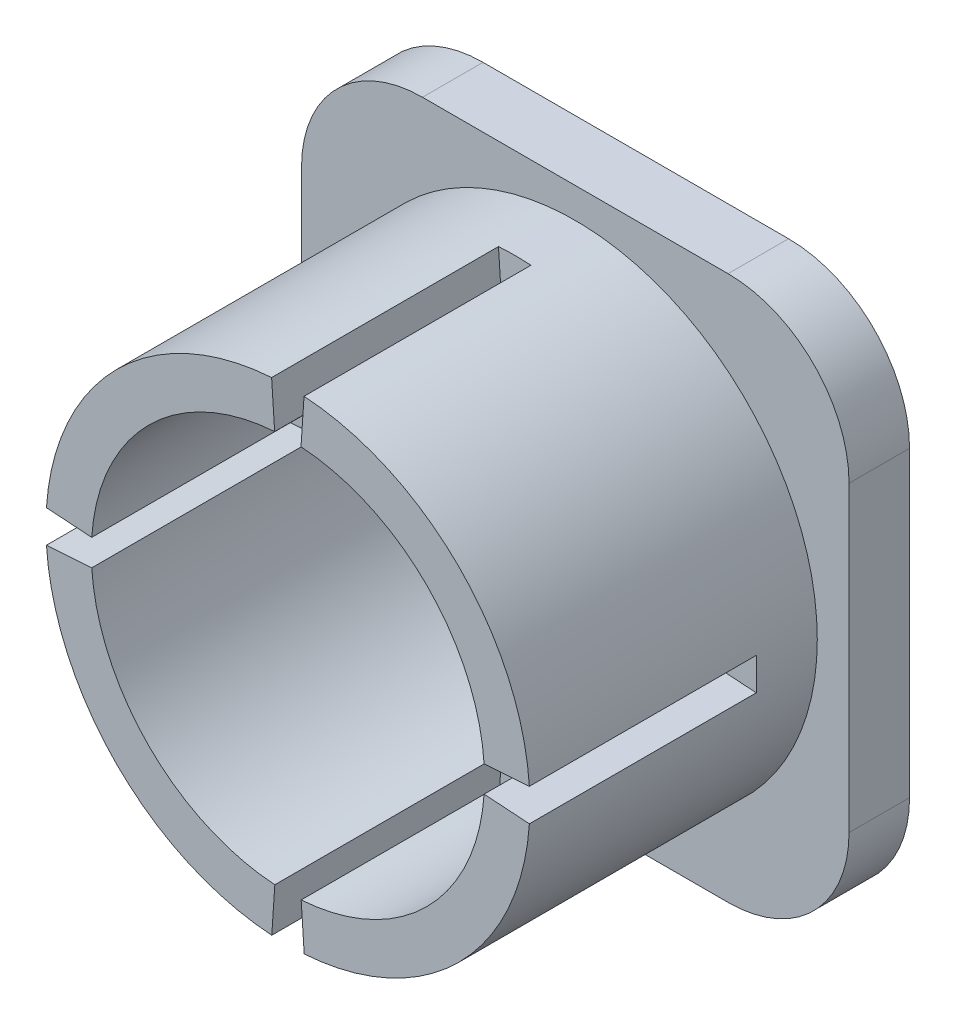
SolidWorks part; units mm, degrees
ref_plane "Front Plane" through (0, 0, 0) normal (0, 0, 1) x (1, 0, 0)
ref_plane "Top Plane" through (0, 0, 0) normal (0, 1, 0) x (1, 0, 0)
ref_plane "Right Plane" through (0, 0, 0) normal (1, 0, 0) x (0, 0, -1)
sketch "Sketch1" plane through (0, 0, 0) normal (0, 0, 1) x (1, 0, 0)
  line L12 (-5.05, 9.0001) -> (5.05, 9.0001)
  line L13 (-9.05, 5.0001) -> (-9.05, -5.0001)
  line L14 (-5.05, -9.0001) -> (5.05, -9.0001)
  line L15 (9.05, 5.0001) -> (9.05, -5.0001)
  line L16 (-9.05, 9.0001) -> (9.05, -9.0001) construction
  line L17 (-9.05, -9.0001) -> (9.05, 9.0001) construction
  arc A4 (-9.05, -5.0001) -> (-5.05, -9.0001) centre (-5.05, -5.0001) ccw
  arc A5 (5.05, -9.0001) -> (9.05, -5.0001) centre (5.05, -5.0001) ccw
  arc A6 (5.05, 9.0001) -> (9.05, 5.0001) centre (5.05, 5.0001) cw
  arc A7 (-5.05, 9.0001) -> (-9.05, 5.0001) centre (-5.05, 5.0001) ccw
  point P0 (0, 0)
  dimension "D2" = 4
  dimension "D1" = 9.05
extrude "Boss-Extrude1" add sketch "Sketch1" along normal blind 0.0001
sketch "Sketch2" plane through (0, 0, 0) normal (0, 0, 1) x (1, 0, 0)
  line L0 (-5.05, 9.0001) -> (5.05, 9.0001)
  line L1 (-9.05, 5.0001) -> (-9.05, -5.0001)
  line L2 (-5.05, -9.0001) -> (5.05, -9.0001)
  line L3 (9.05, 5.0001) -> (9.05, -5.0001)
  line L4 (-9.05, 9.0001) -> (9.05, -9.0001) construction
  line L5 (-9.05, -9.0001) -> (9.05, 9.0001) construction
  arc A0 (-9.05, -5.0001) -> (-5.05, -9.0001) centre (-5.05, -5.0001) ccw
  arc A1 (5.05, -9.0001) -> (9.05, -5.0001) centre (5.05, -5.0001) ccw
  arc A2 (5.05, 9.0001) -> (9.05, 5.0001) centre (5.05, 5.0001) cw
  arc A3 (-5.05, 9.0001) -> (-9.05, 5.0001) centre (-5.05, 5.0001) ccw
  point P0 (0, 0)
  dimension "D2" = 4
  dimension "D1" = 9.05
extrude "Boss-Extrude2" add sketch "Sketch2" along normal blind 2
sketch "Sketch3" plane through (0, 0, 2) normal (0, 0, 1) x (1, 0, 0)
  line L1 (-5.05, 9.0001) -> (5.05, 9.0001)
  line L2 (-9.05, 5.0001) -> (-9.05, -5.0001)
  line L3 (-5.05, -9.0001) -> (5.05, -9.0001)
  line L4 (9.05, 5.0001) -> (9.05, -5.0001)
  line L5 (-9.05, 9.0001) -> (9.05, -9.0001) construction
  line L6 (-9.05, -9.0001) -> (9.05, 9.0001) construction
  arc A0 (-9.05, -5.0001) -> (-5.05, -9.0001) centre (-5.05, -5.0001) ccw
  arc A1 (5.05, -9.0001) -> (9.05, -5.0001) centre (5.05, -5.0001) ccw
  arc A2 (5.05, 9.0001) -> (9.05, 5.0001) centre (5.05, 5.0001) cw
  arc A3 (-5.05, 9.0001) -> (-9.05, 5.0001) centre (-5.05, 5.0001) ccw
  point P0 (0, 0)
  dimension "D2" = 4
  dimension "D1" = 9.05
extrude "Boss-Extrude3" add sketch "Sketch3" along normal blind 0.0001
sketch "Sketch4" plane through (0, 0, 2.0001) normal (0, 0, 1) x (1, 0, 0)
  circle A1 centre (0, 0) radius 8
  dimension "D2" = 16
extrude "Boss-Extrude4" add sketch "Sketch4" along normal blind 9.5
sketch "Sketch5" plane through (0, 0, 2.0001) normal (0, 0, 1) x (1, 0, 0)
  circle A0 centre (0, 0) radius 6.5
  dimension "D1" = 13
extrude "Cut-Extrude1" cut sketch "Sketch5" against normal mid plane 50
sketch "Sketch15" plane through (0, 0, 11.5001) normal (0, 0, 1) x (1, 0, 0)
  line L1 (-0.5528, 8.1871) -> (-0.0028, 0.0033)
  line L3 (0.5472, 8.1871) -> (-0.0028, 0.0033)
  line L4 (-0.5528, 8.1871) -> (-0.626, 9.0001)
  line L5 (5.05, 9.0001) -> (-5.05, 9.0001) construction
  line L6 (-0.626, 9.0001) -> (0.6172, 9.0001)
  line L7 (0.6172, 9.0001) -> (0.5472, 8.1871)
  dimension "D3" = 0.0732
  dimension "D4" = 0.07
extrude "Cut-Extrude4" cut sketch "Sketch15" against normal blind 7.5 contours L1 L3 L7 L6 L4
pattern_circular "CirPattern2" count 4 over 360 about axis through (0, 0, 0) along (0, 0, 1) of "Cut-Extrude4"
